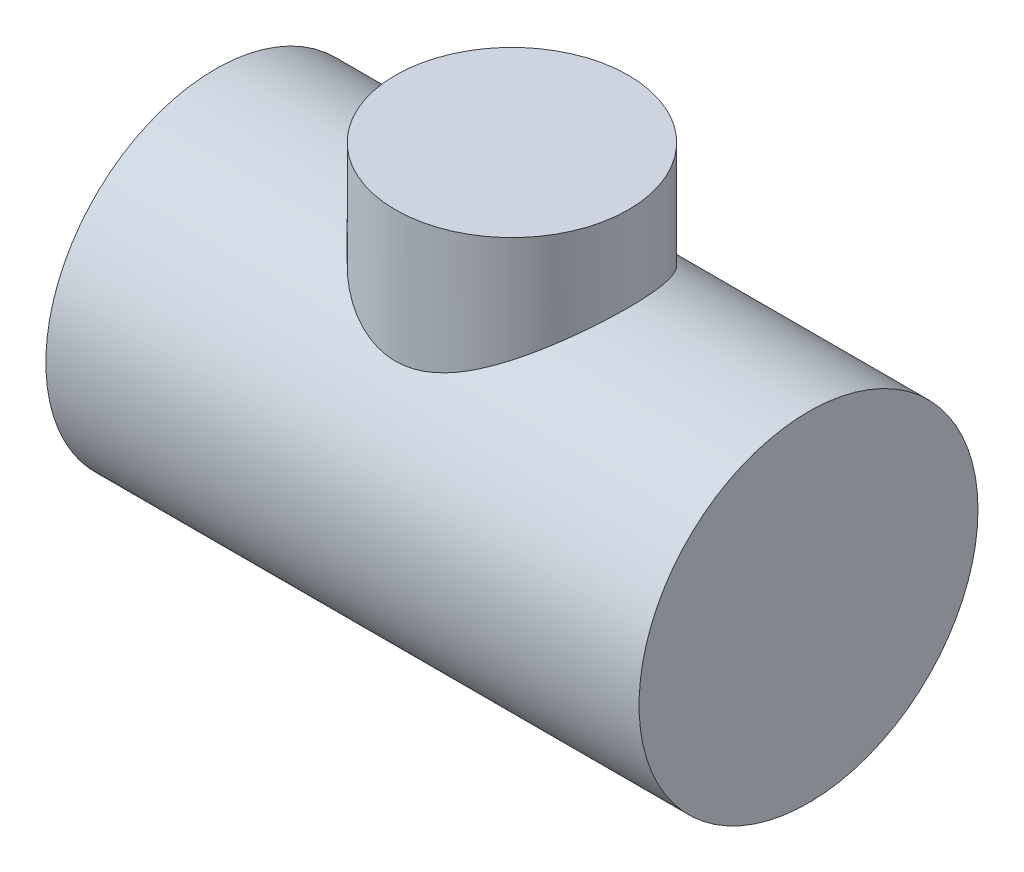
SolidWorks part; units mm, degrees
ref_plane "Front Plane" through (0, 0, 0) normal (0, 0, 1) x (1, 0, 0)
ref_plane "Top Plane" through (0, 0, 0) normal (0, 1, 0) x (1, 0, 0)
ref_plane "Right Plane" through (0, 0, 0) normal (1, 0, 0) x (0, 0, -1)
sketch "Sketch1" plane through (0, 0, 0) normal (1, 0, 0) x (0, 0, -1)
  circle A0 centre (0, 0) radius 50.8
  dimension "D1" = 101.6
extrude "Boss-Extrude1" add sketch "Sketch1" along normal mid plane 177.8
sketch "Sketch2" plane through (0, 0, 0) normal (0, 1, 0) x (1, 0, 0)
  circle A0 centre (0, 0) radius 34.925
  dimension "D1" = 69.85
extrude "Boss-Extrude2" add sketch "Sketch2" along normal blind 76.2
